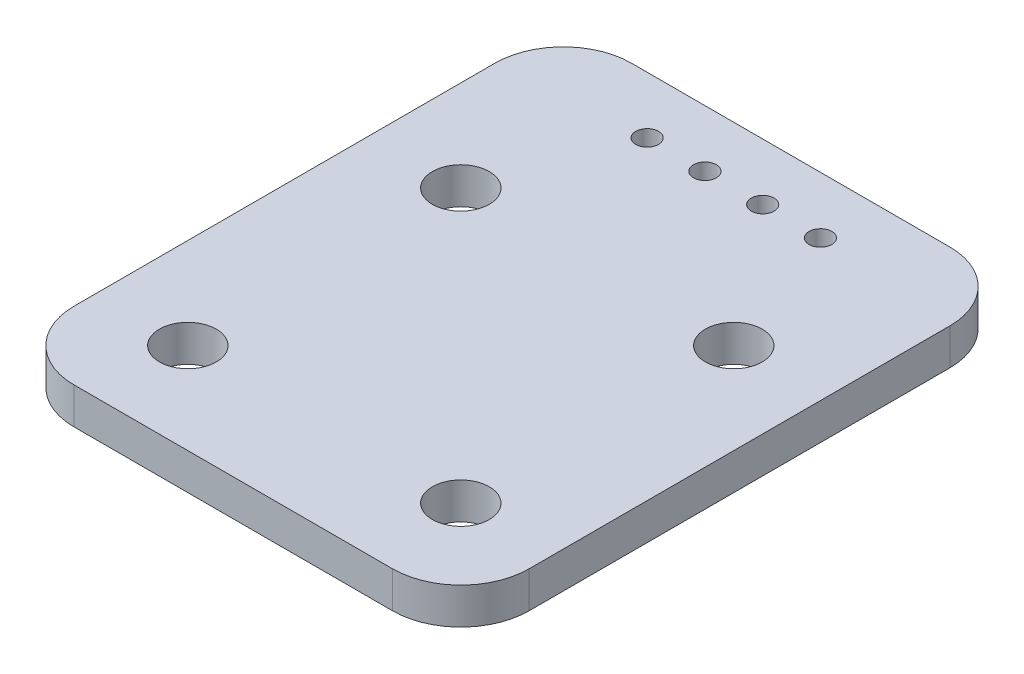
SolidWorks part; units mm, degrees
ref_plane "Front Plane" through (0, 0, 0) normal (0, 0, 1) x (1, 0, 0)
ref_plane "Top Plane" through (0, 0, 0) normal (0, 1, 0) x (1, 0, 0)
ref_plane "Right Plane" through (0, 0, 0) normal (1, 0, 0) x (0, 0, -1)
sketch "Sketch1" plane through (0, 0, 0) normal (0, 1, 0) x (1, 0, 0)
  line L1 (-10, 12.25) -> (10, 12.25)
  line L2 (-10, 12.25) -> (-10, -12.25)
  line L3 (-10, -12.25) -> (10, -12.25)
  line L4 (10, 12.25) -> (10, -12.25)
  line L5 (-10, 12.25) -> (10, -12.25) construction
  line L6 (-10, -12.25) -> (10, 12.25) construction
  point P0 (0, 0)
  dimension "D1" = 20
  dimension "D2" = 24.5
extrude "Boss-Extrude1" add sketch "Sketch1" along normal blind 1.6
sketch "Sketch2" plane through (0, 1.6, 0) normal (0, 1, 0) x (1, 0, 0)
  line L0 (-10, -12.25) -> (10, -12.25) construction
  line L1 (-6, -8.25) -> (6, -8.25) construction
  line L2 (-6, -8.25) -> (-6, 3.75) construction
  line L3 (-6, 3.75) -> (6, 3.75) construction
  line L4 (6, -8.25) -> (6, 3.75) construction
  line L5 (-6, -8.25) -> (6, 3.75) construction
  line L6 (-6, 3.75) -> (6, -8.25) construction
  line L7 (0, 12.25) -> (0, 9.75) construction
  line L8 (10, 12.25) -> (-10, 12.25) construction
  line L9 (-3.81, 9.75) -> (-1.27, 9.75) construction
  line L10 (-1.27, 9.75) -> (1.27, 9.75) construction
  line L11 (1.27, 9.75) -> (3.81, 9.75) construction
  circle A0 centre (-6, -8.25) radius 1.25
  circle A1 centre (6, -8.25) radius 1.25
  circle A2 centre (6, 3.75) radius 1.25
  circle A3 centre (-6, 3.75) radius 1.25
  circle A8 centre (-3.81, 9.75) radius 0.5
  circle A9 centre (-1.27, 9.75) radius 0.5
  circle A10 centre (1.27, 9.75) radius 0.5
  circle A11 centre (3.81, 9.75) radius 0.5
  point P4 (0, -2.25)
  point P24 (0, 0)
  dimension "D1" = 2.5
  dimension "D6" = 1
  dimension "D2" = 12
  dimension "D3" = 12
  dimension "D4" = 10
  dimension "D5" = 2.5
  dimension "D7" = 2.54
extrude "Cut-Extrude1" cut sketch "Sketch2" against normal through all both and the other way through all
sketch "Sketch3" plane through (0, 1.6, 0) normal (0, 1, 0) x (1, 0, 0)
  line L1 (-5, -4.75) -> (5, -4.75)
  line L2 (-5, -4.75) -> (-5, 0.25)
  line L3 (-5, 0.25) -> (5, 0.25)
  line L4 (5, -4.75) -> (5, 0.25)
  line L5 (-5, -4.75) -> (5, 0.25) construction
  line L6 (-5, 0.25) -> (5, -4.75) construction
  point P0 (0, -2.25)
  dimension "D1" = 5
  dimension "D2" = 10
fillet "Fillet1" radius 3 4 edges at (10, 0.8, 12.25) (-10, 0.8, 12.25) (10, 0.8, -12.25) (-10, 0.8, -12.25)
